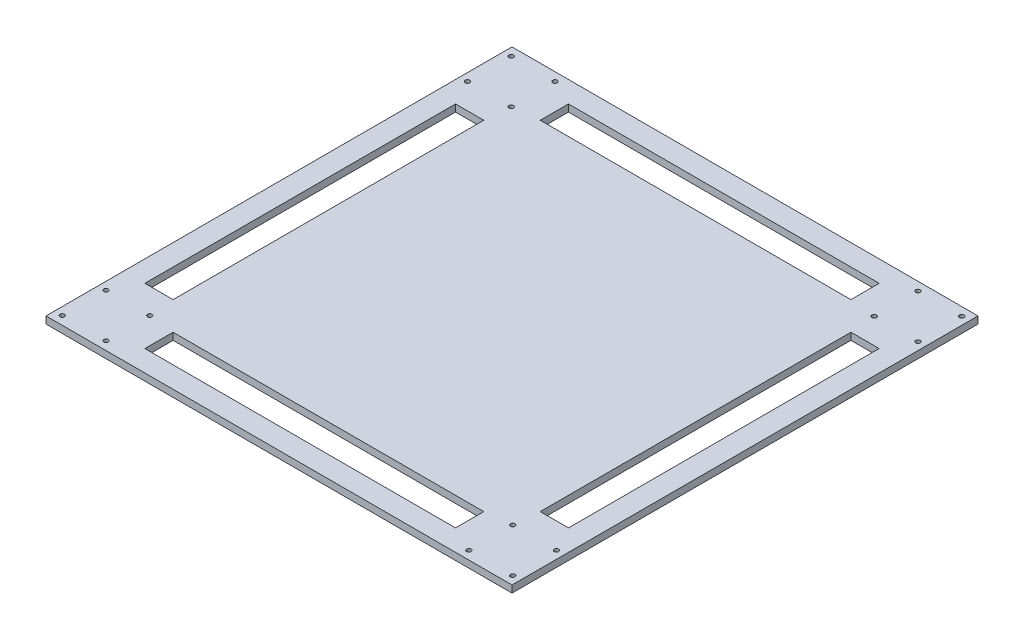
SolidWorks part; units mm, degrees
ref_plane "前视基准面" through (0, 0, 0) normal (0, 0, 1) x (1, 0, 0)
ref_plane "上视基准面" through (0, 0, 0) normal (0, 1, 0) x (1, 0, 0)
ref_plane "右视基准面" through (0, 0, 0) normal (1, 0, 0) x (0, 0, -1)
other "Configuration Table"
sketch "草图1" plane through (0, 0, 0) normal (0, 1, 0) x (1, 0, 0)
  line L1 (165, -165) -> (-165, -165)
  line L2 (165, -165) -> (165, 165)
  line L3 (165, 165) -> (-165, 165)
  line L4 (-165, -165) -> (-165, 165)
  line L5 (165, -165) -> (-165, 165) construction
  line L6 (165, 165) -> (-165, -165) construction
  point P0 (0, 0)
  dimension "D1" = 330
  dimension "D2" = 330
extrude "凸台-拉伸1" add sketch "草图1" along normal blind 5
sketch "草图2" plane through (0, 5, 0) normal (0, 1, 0) x (1, 0, 0)
  circle A0 centre (-159.5, 159) radius 1.6
  circle A1 centre (-128.5, 159) radius 1.6
  circle A2 centre (-159.5, 128) radius 1.6022
  circle A3 centre (-128.5, 128) radius 1.6
  circle A4 centre (128.5, 159) radius 1.6
  circle A5 centre (159.5, 159) radius 1.6
  circle A6 centre (128.5, 128) radius 1.6
  circle A7 centre (159.5, 128) radius 1.6
  circle A8 centre (128.5, -128) radius 1.6
  circle A9 centre (159.5, -128) radius 1.6
  circle A10 centre (159.5, -159) radius 1.6
  circle A11 centre (128.5, -159) radius 1.6
  circle A12 centre (-128.5, -159) radius 1.6
  circle A13 centre (-159.5, -159) radius 1.6
  circle A14 centre (-159.5, -128) radius 1.6
  circle A15 centre (-128.5, -128) radius 1.6
extrude "切除-拉伸1" cut sketch "草图2" against normal through all
sketch "草图3" plane through (0, 5, 0) normal (0, 1, 0) x (1, 0, 0)
  line L0 (-110, 60) -> (-110, 40)
  line L1 (110, -110) -> (-110, -110) construction
  line L2 (110, -110) -> (110, 110) construction
  line L3 (110, 110) -> (-110, 110) construction
  line L4 (-110, -110) -> (-110, 110) construction
  line L5 (110, -110) -> (-110, 110) construction
  line L6 (110, 110) -> (-110, -110) construction
  line L7 (-110, 110) -> (110, 110)
  line L8 (-110, 110) -> (-110, 90)
  line L9 (-110, 90) -> (110, 90)
  line L10 (110, 110) -> (110, 90)
  line L11 (-110, 60) -> (110, 60)
  line L12 (110, 60) -> (110, 40)
  line L13 (-110, 40) -> (110, 40)
  line L14 (-110, 10) -> (-110, -10)
  line L15 (-110, 10) -> (110, 10)
  line L16 (110, 10) -> (110, -10)
  line L17 (-110, -10) -> (110, -10)
  line L18 (-110, -40) -> (-110, -60)
  line L19 (-110, -40) -> (110, -40)
  line L20 (110, -40) -> (110, -60)
  line L21 (-110, -60) -> (110, -60)
  line L22 (-110, -90) -> (-110, -110)
  line L23 (-110, -90) -> (110, -90)
  line L24 (110, -90) -> (110, -110)
  line L25 (-110, -110) -> (110, -110)
  point P0 (0, 0)
  dimension "D1" = 220
  dimension "D2" = 220
  dimension "D3" = 20
  dimension "D4" = 5
extrude "切除-拉伸2" cut sketch "草图3" against normal through all contours L10 L7 L8 L9 | L0 L13 L12 L11 | L14 L17 L16 L15 | L18 L21 L20 L19 | L22 L25 L24 L23
sketch "草图4" plane through (0, 5, 0) normal (0, 1, 0) x (1, 0, 0)
  line L0 (-110, 110) -> (-110, 90) construction
  line L1 (-150, 110) -> (-130, 110)
  line L2 (-150, 110) -> (-150, -110)
  line L3 (-150, -110) -> (-130, -110)
  line L4 (-130, 110) -> (-130, -110)
  line L5 (0, 110) -> (0, 79.1501) construction
  line L6 (-110, 110) -> (110, 110) construction
  line L7 (150, -110) -> (130, -110)
  line L8 (130, 110) -> (130, -110)
  line L9 (150, 110) -> (130, 110)
  line L10 (150, 110) -> (150, -110)
  dimension "D1" = 20
  dimension "D2" = 220
  dimension "D3" = 20
extrude "切除-拉伸3" cut sketch "草图4" against normal through all
sketch "草图7" plane through (0, 5, 0) normal (0, 1, 0) x (1, 0, 0)
  line L0 (-110, 110) -> (110, 110) construction
  line L1 (-110, 150) -> (110, 150)
  line L2 (-110, 150) -> (-110, 130)
  line L3 (-110, 130) -> (110, 130)
  line L4 (110, 150) -> (110, 130)
  line L5 (0, 0) -> (31.0627, 0) construction
  line L6 (-110, -130) -> (110, -130)
  line L7 (110, -150) -> (110, -130)
  line L8 (-110, -150) -> (110, -150)
  line L9 (-110, -150) -> (-110, -130)
  dimension "D1" = 20
  dimension "D2" = 220
  dimension "D3" = 20
extrude "切除-拉伸4" cut sketch "草图7" against normal through all
sketch "草图8" plane through (0, 5, 0) normal (0, 1, 0) x (1, 0, 0)
  line L0 (120, 0) -> (-120, 0)
  line L1 (0, -120) -> (0, 120)
  point P4 (0, 0)
  point P8 (0, 0)
sketch "草图9" plane through (0, 5, 0) normal (0, 1, 0) x (1, 0, 0)
  line L1 (-117.6798, 117.0824) -> (121.8613, 117.0824)
  line L2 (-117.6798, 117.0824) -> (-117.6798, -116.4851)
  line L3 (-117.6798, -116.4851) -> (121.8613, -116.4851)
  line L4 (121.8613, 117.0824) -> (121.8613, -116.4851)
extrude "凸台-拉伸2" add sketch "草图9" against normal blind 5
